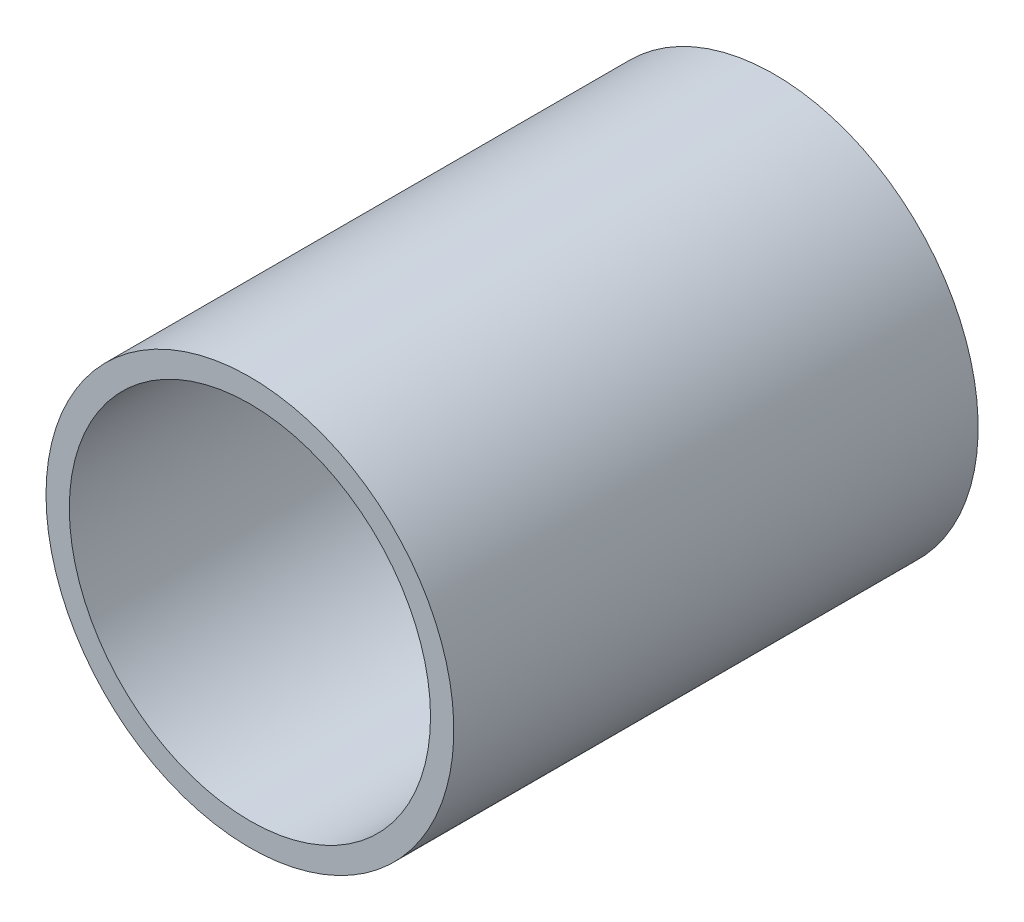
SolidWorks part; units mm, degrees
material "Acrylic (Medium-high impact)"
ref_plane "Front Plane" through (0, 0, 0) normal (0, 0, 1) x (1, 0, 0)
ref_plane "Top Plane" through (0, 0, 0) normal (0, 1, 0) x (1, 0, 0)
ref_plane "Right Plane" through (0, 0, 0) normal (1, 0, 0) x (0, 0, -1)
sketch "Sketch1" plane through (0, 0, 0) normal (0, 0, 1) x (1, 0, 0)
  circle A0 centre (0, 0) radius 35
  circle A1 centre (0, 0) radius 31
  dimension "D1" = 62
  dimension "D2" = 70
extrude "Boss-Extrude1" add sketch "Sketch1" along normal blind 90
